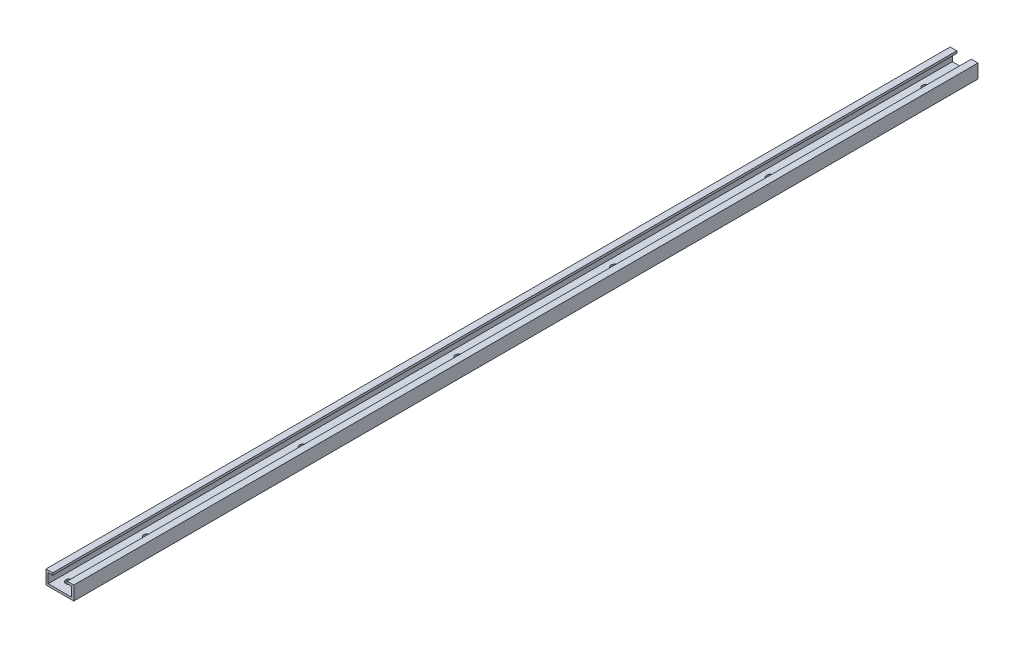
SolidWorks part; units mm, degrees
ref_plane "Plan de face" through (0, 0, 0) normal (0, 0, 1) x (1, 0, 0)
ref_plane "Plan de dessus" through (0, 0, 0) normal (0, 1, 0) x (1, 0, 0)
ref_plane "Plan de droite" through (0, 0, 0) normal (1, 0, 0) x (0, 0, -1)
sketch "Esquisse1" plane through (0, 0, 0) normal (0, 0, 1) x (1, 0, 0)
  line L0 (-6.5, 12.5) -> (-12.5, 12.5)
  line L1 (-12.5, 12.5) -> (-12.5, 0)
  line L2 (-12.5, 0) -> (12.5, 0)
  line L3 (12.5, 0) -> (12.5, 12.5)
  line L4 (12.5, 12.5) -> (6.5, 12.5)
  line L5 (0, 8.7838) -> (0, -4.9459) construction
  line L6 (-6.5, 10.5) -> (-10.5, 10.5)
  line L7 (-10.5, 10.5) -> (-10.5, 2)
  line L8 (-10.5, 2) -> (10.5, 2)
  line L9 (10.5, 2) -> (10.5, 10.5)
  line L10 (10.5, 10.5) -> (6.5, 10.5)
  line L11 (-6.5, 12.5) -> (-6.5, 10.5)
  line L12 (6.5, 12.5) -> (6.5, 10.5)
  dimension "D1" = 13
  dimension "D2" = 25
  dimension "D4" = 2
  dimension "D3" = 12.5
extrude "Boss.-Extru.1" add sketch "Esquisse1" along normal blind 813
hole_wizard "Dégagement M61" positions "Esquisse3" profile "Esquisse2" hole size "M6" standard "JIS" end condition through all
sketch "Esquisse3" plane through (0, 0, 0) normal (0, -1, 0) x (-1, 0, 0)
  point P0 (2.4063, -801.8069)
sketch "Esquisse2" plane through (-2.4063, 0, 801.8069) normal (1, 0, 0) x (0, 0, -1)
  line L0 (0, 0) -> (0, 12.5)
  line L1 (0, 12.5) -> (3.3, 12.5)
  line L2 (3.3, 12.5) -> (3.3, 0)
  line L5 (3.3, 0) -> (0, 0)
  line L11 (0, -6.35) -> (0, 107.95) construction
  dimension "Diamètre du perçage jusqu'au prochain" = 6.6
  dimension "Profondeur du perçage jusqu'au prochain" = 12.5
pattern_linear "Répétition linéaire1" count 12 spacing 70 along (0, 0, -1) skipping (2, 0), (4, 0), (6, 0), (8, 0), (10, 0) of "Dégagement M61"
